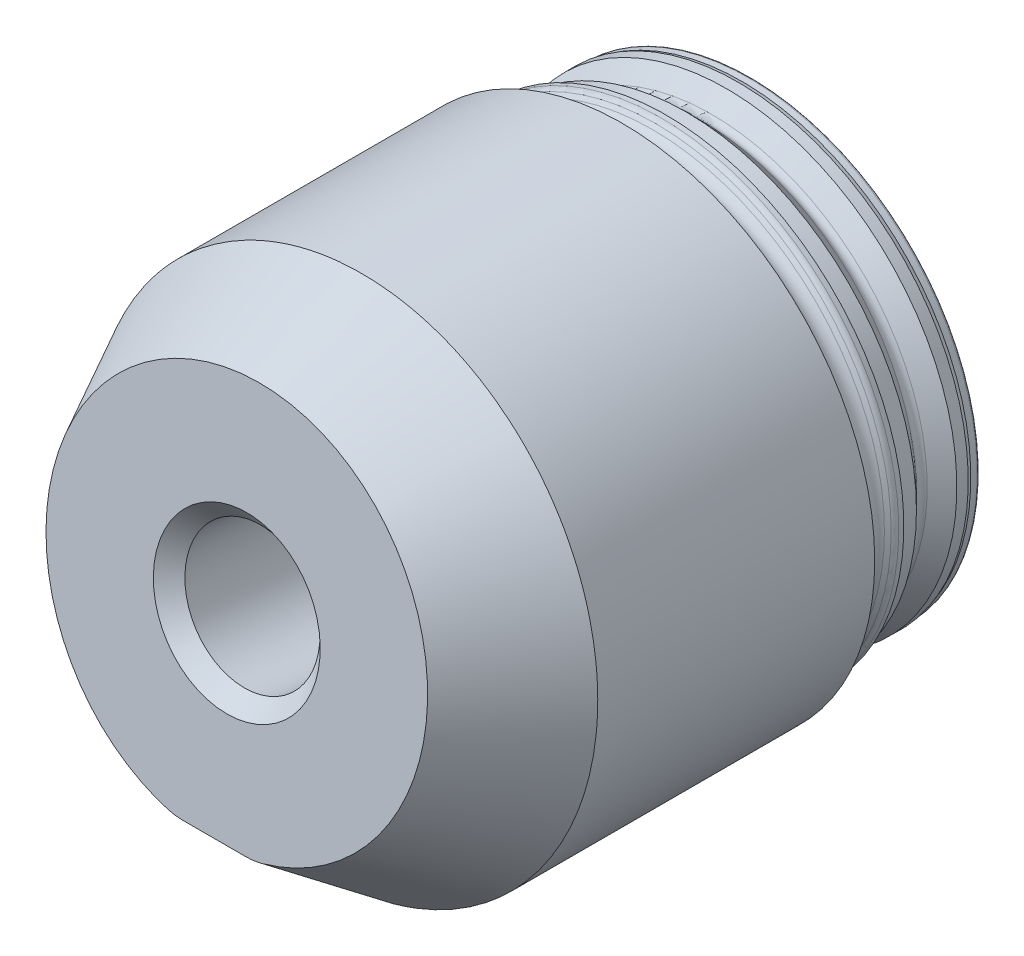
SolidWorks part; units mm, degrees
ref_plane "front" through (0, 0, 0) normal (0, 0, 1) x (1, 0, 0)
ref_plane "top" through (0, 0, 0) normal (0, 1, 0) x (1, 0, 0)
ref_plane "right" through (0, 0, 0) normal (1, 0, 0) x (0, 0, -1)
sketch "L2D-00 Layout" plane through (0, 0, 0) normal (1, 0, 0) x (0, 0, -1)
  line L0 (-43.1774, 2.0979) -> (-40.3575, 25.4) construction
  line L1 (27.7667, 0) -> (-53.34, 0) construction
  line L2 (-44.131, -5.7821) -> (-6.3069, -10.3593)
  line L3 (0, 23.1394) -> (2.032, 23.1394)
  line L4 (8.509, 22.7647) -> (8.509, 19.05)
  line L5 (-4.425, 25.4) -> (-45.466, 25.4)
  line L6 (-45.466, 25.4) -> (-45.466, -25.4)
  line L7 (-45.466, 0) -> (-12.1157, 0)
  line L8 (-0.508, 23.9014) -> (0, 23.9014)
  line L9 (0, 23.9014) -> (0, 23.1394)
  line L10 (8.509, 19.05) -> (-7.366, 19.05)
  line L11 (-7.366, -19.05) -> (-12.1157, 0)
  line L12 (-3.3859, -23.6001) -> (-4.425, -25.4)
  line L13 (6.096, -23.1394) -> (7.239, -23.1394)
  line L14 (3.5252, -21.6462) -> (2.032, -23.1394)
  line L15 (6.096, -23.1394) -> (4.6028, -21.6462)
  line L17 (-0.6185, -3.0523) -> (-6.3069, -10.3593)
  line L18 (-43.1774, 2.0979) -> (-0.6185, -3.0523) construction
  line L19 (-7.366, 19.05) -> (-12.1157, 0)
  line L20 (7.239, 23.1394) -> (7.62, 23.0187)
  line L21 (7.62, 23.0187) -> (8.255, 23.0187)
  line L22 (-1.0468, -23.6782) -> (-1.388, -23.3371)
  line L23 (7.62, -23.0187) -> (8.255, -23.0187)
  line L24 (7.239, -23.1394) -> (7.62, -23.0187)
  line L25 (8.509, -19.05) -> (-7.366, -19.05)
  line L26 (8.509, 19.05) -> (8.509, -19.05)
  line L28 (-1.0468, 23.6782) -> (-1.388, 23.3371)
  line L29 (6.096, 23.1394) -> (4.6028, 21.6462)
  line L30 (3.5252, 21.6462) -> (2.032, 23.1394)
  line L31 (6.096, 23.1394) -> (7.239, 23.1394)
  line L32 (0, -23.9014) -> (0, -23.1394)
  line L33 (-0.508, -23.9014) -> (0, -23.9014)
  line L34 (-4.425, -25.4) -> (-45.466, -25.4)
  line L35 (-3.3859, 23.6001) -> (-4.425, 25.4)
  line L36 (8.509, -22.7647) -> (8.509, -19.05)
  line L37 (0, -23.1394) -> (2.032, -23.1394)
  line L38 (-43.1774, 2.0979) -> (-45.466, -16.8141) construction
  line L39 (-0.6185, -3.0523) -> (-4.3998, 5.4007)
  line L40 (-42.2238, 9.9779) -> (-4.3998, 5.4007)
  line L44 (-45.466, -16.8141) -> (-31.8818, -18.4556)
  arc A0 (4.6028, 21.6462) -> (3.5252, 21.6462) centre (4.064, 22.185) cw
  circle A1 centre (4.064, -23.3561) radius 1.59 construction
  arc A2 (8.255, 23.0187) -> (8.509, 22.7647) centre (8.255, 22.7647) cw
  arc A3 (-0.508, 23.9014) -> (-1.0468, 23.6782) centre (-0.508, 23.1394) ccw
  arc A4 (-1.388, 23.3371) -> (-3.3859, 23.6001) centre (-2.286, 24.2351) cw
  circle A5 centre (4.064, 23.3561) radius 1.59 construction
  arc A6 (-1.388, -23.3371) -> (-3.3859, -23.6001) centre (-2.286, -24.2351) ccw
  arc A7 (-0.508, -23.9014) -> (-1.0468, -23.6782) centre (-0.508, -23.1394) cw
  arc A8 (8.255, -23.0187) -> (8.509, -22.7647) centre (8.255, -22.7647) ccw
  arc A9 (4.6028, -21.6462) -> (3.5252, -21.6462) centre (4.064, -22.185) ccw
  point P48 (-25.8414, 0)
  point P51 (4.064, 24.9461)
  point P63 (4.064, -24.9461)
  dimension "D2" = 50.8
  dimension "D26" = 45
  dimension "D29" = 0.762
  dimension "D30" = 1.27
  dimension "D3" = 0.254
  dimension "D5" = 46.2788
  dimension "D8" = 8.509
  dimension "D32" = 0.762
  dimension "D33" = 1.27
  dimension "D36" = 3.1801
  dimension "D4" = 15.875
  dimension "D6" = 38.1
  dimension "D7" = 0.762
  dimension "D9" = 76
  dimension "D10" = 59
  dimension "D11" = 60
  dimension "D12" = 135
  dimension "D13" = 19.05
  dimension "D14" = 23.4721
  dimension "D15" = 17.4625
  dimension "D17" = 83.1
  dimension "D19" = 15.875
  dimension "D20" = 38.1
  dimension "D21" = 25.8414
  dimension "D22" = 53.975
  dimension "D23" = 0.01
  dimension "D25" = 0.889
  dimension "D27" = 4.064
  dimension "D28" = 2.413
  dimension "D31" = 46.0375
  dimension "D34" = 2.286
  dimension "D35" = 0.508
  dimension "D37" = 4.0894
  dimension "D38" = 49.8922
  dimension "D39" = 12.934
ref_plane "RPL-00 Plane for notch." through (0, -3.0523, 0.6185) normal (0, -0.1201, -0.9928) x (-1, 0, 0)
sketch "Sketch3" plane through (0, 0, 0) normal (1, 0, 0) x (0, 0, -1)
  line L0 (27.7667, 0) -> (-53.34, 0) construction
  line L8 (27.7667, 0) -> (-53.34, 0) construction
  line L9 (-45.466, 0) -> (-12.1157, 0) construction
  line L10 (-45.466, 25.4) -> (-45.466, -25.4) construction
  line L11 (-4.425, 25.4) -> (-45.466, 25.4) construction
  line L12 (-3.3859, 23.6001) -> (-4.425, 25.4) construction
  line L13 (-1.0468, 23.6782) -> (-1.388, 23.3371) construction
  line L14 (-0.508, 23.9014) -> (0, 23.9014) construction
  line L15 (0, 23.9014) -> (0, 23.1394) construction
  line L16 (0, 23.1394) -> (2.032, 23.1394) construction
  line L17 (3.5252, 21.6462) -> (2.032, 23.1394) construction
  line L18 (6.096, 23.1394) -> (4.6028, 21.6462) construction
  line L24 (6.096, 23.1394) -> (7.239, 23.1394) construction
  line L25 (7.239, 23.1394) -> (7.62, 23.0187) construction
  line L26 (7.62, 23.0187) -> (8.255, 23.0187) construction
  line L27 (8.509, 22.7647) -> (8.509, 19.05) construction
  line L28 (-7.366, 19.05) -> (-12.1157, 0) construction
  line L29 (8.509, 19.05) -> (-7.366, 19.05) construction
  line L30 (-45.466, 0) -> (-12.1157, 0)
  line L31 (-45.466, 25.4) -> (-45.466, 0)
  line L32 (-4.425, 25.4) -> (-45.466, 25.4)
  line L33 (-3.3859, 23.6001) -> (-4.425, 25.4)
  line L34 (-1.0468, 23.6782) -> (-1.388, 23.3371)
  line L35 (-0.508, 23.9014) -> (0, 23.9014)
  line L36 (0, 23.9014) -> (0, 23.1394)
  line L37 (0, 23.1394) -> (2.032, 23.1394)
  line L38 (3.5252, 21.6462) -> (2.032, 23.1394)
  line L39 (6.096, 23.1394) -> (4.6028, 21.6462)
  line L40 (6.096, 23.1394) -> (7.239, 23.1394)
  line L41 (7.239, 23.1394) -> (7.62, 23.0187)
  line L42 (7.62, 23.0187) -> (8.255, 23.0187)
  line L43 (8.509, 22.7647) -> (8.509, 19.05)
  line L44 (-7.366, 19.05) -> (-12.1157, 0)
  line L45 (8.509, 19.05) -> (-7.366, 19.05)
  arc A1 (-3.3859, 23.6001) -> (-1.388, 23.3371) centre (-2.286, 24.2351) ccw construction
  arc A2 (-0.508, 23.9014) -> (-1.0468, 23.6782) centre (-0.508, 23.1394) ccw construction
  arc A3 (3.5252, 21.6462) -> (4.6028, 21.6462) centre (4.064, 22.185) ccw construction
  arc A4 (8.509, 22.7647) -> (8.255, 23.0187) centre (8.255, 22.7647) ccw construction
  arc A5 (-3.3859, 23.6001) -> (-1.388, 23.3371) centre (-2.286, 24.2351) ccw
  arc A6 (-0.508, 23.9014) -> (-1.0468, 23.6782) centre (-0.508, 23.1394) ccw
  arc A7 (3.5252, 21.6462) -> (4.6028, 21.6462) centre (4.064, 22.185) ccw
  arc A8 (8.509, 22.7647) -> (8.255, 23.0187) centre (8.255, 22.7647) ccw
revolve "FBR-00 Basic blank revolve." add sketch "Sketch3" angle 360 about L8
sketch "Sketch19" plane through (0, 0, 0) normal (1, 0, 0) x (0, 0, -1)
  line L0 (-43.1774, 2.0979) -> (-40.3575, 25.4) construction
  line L1 (-47.5365, -33.9238) -> (-39.2605, 34.4651)
extrude "FCE-00 Trim end." cut sketch "Sketch19" against normal through all and the other way through all
hole_wizard "5/8-11 Tapped Hole1" positions "3DSketch1" profile "Sketch20" tap size "5/8-11" standard "Ansi Inch"
sketch3d "3DSketch1"
  line L0 (0, 2.0979, 43.1774) -> (0, -3.0523, 0.6185) construction
  point P3 (0, 2.0979, 43.1774)
sketch "Sketch20" plane through (0, 2.0979, 43.1774) normal (1, 0, 0) x (0, -0.9928, 0.1201)
  line L0 (0, 0) -> (0, 44.1728)
  line L1 (0, 44.1728) -> (6.7462, 40.1193)
  line L2 (6.7462, 40.1193) -> (6.7462, 1.585)
  line L3 (6.7462, 1.585) -> (8.3312, 0)
  line L5 (8.3312, 0) -> (0, 0)
  line L6 (-6.7462, 1.585) -> (-8.3312, 0) construction
  line L10 (0, 44.1728) -> (-6.7462, 40.1193) construction
  line L11 (0, -6.35) -> (0, 107.95) construction
  dimension "Hole Dia." = 13.4925
  dimension "Hole Depth" = 40.1193
  dimension "Near C'Sink Dia." = 16.6624
  dimension "Near C'Sink Angle" = 90
  dimension "Drill Angle" = 118
sketch "Sketch23" plane through (0, 5.1799, 42.8044) normal (0, 0.1201, 0.9928) x (1, 0, 0)
  line L0 (-25.654, -4.533) -> (-25.654, -2.3425)
  line L2 (25.654, -2.3425) -> (25.654, -6.3158)
  arc A0 (25.654, -2.3425) -> (-25.654, -2.3425) centre (0, -2.3425) cw
  circle A1 centre (0, -3.1045) radius 19.05 construction
  dimension "D2" = 0.762
  dimension "D3" = 38.1
  dimension "D1" = 51.308
extrude "FCE-00 Side cut arc." [suppressed] cut sketch "Sketch23" against normal through all and the other way through all flip side to cut
ref_plane "RPL-00 Plane for bevel sweep." through (0, -16.8141, 45.466) normal (0, -0.12, -0.9928) x (-1, 0, 0)
sketch "Sketch22" plane through (0, -16.8141, 45.466) normal (0, -0.12, -0.9928) x (-1, 0, 0)
  line L0 (-3.175, 0.4033) -> (3.175, 0.4033)
  arc A0 (-3.175, 0.4033) -> (-4.7625, 0.6049) centre (-3.175, 6.7533) cw
  arc A1 (3.175, 0.4033) -> (4.7625, 0.6049) centre (3.175, 6.7533) ccw
  arc A2 (4.7625, 0.6049) -> (-4.7625, 0.6049) centre (0, 19.05) ccw
  point P7 (0, 0.4033)
  dimension "D2" = 6.35
  dimension "D1" = 19.05
  dimension "D4" = 6.35
sketch "Sketch31" plane through (0, 0, 0) normal (1, 0, 0) x (0, 0, -1)
  line L0 (-46.8837, -15.3134) -> (-11.6977, -41.7222)
  line L1 (-11.6977, -41.7222) -> (-12.4595, -48.0263)
  line L2 (-12.4595, -48.0263) -> (-50.2843, -43.4557)
  line L3 (-50.2843, -43.4557) -> (-46.8837, -15.3134)
  line L6 (-45.466, -16.8141) -> (-31.8818, -18.4556) construction
  point P6 (-45.4176, -16.4138)
  dimension "D1" = 6.35
  dimension "D2" = 38.1
  dimension "D3" = 30
  dimension "D4" = 1.5875
sweep "FCS-00 Bevel." cut profiles "Sketch31" path "Sketch22"
chamfer "FCH-00 Chamfer 0.015" distance 0.381 angle 45
sketch "L2D-00 Text part number." plane through (0, -32.3042, 24.2459) normal (0, -0.7998, 0.6003) x (1, 0, 0)
  line L0 (-1.5875, 23.0921) -> (-1.5875, 11.5858) construction
  text T0 "201" font "Century Gothic" height 3.175
  dimension "D1" = 12.7
  dimension "D2" = 1.5875
sketch "Sketch10" plane through (0, 0, 0) normal (0, 1, 0) x (1, 0, 0)
  line L0 (0, 38.5125) -> (0, -115.1189)
extrude "FCE-00 Section." [suppressed] cut sketch "Sketch10" against normal through all and the other way through all
